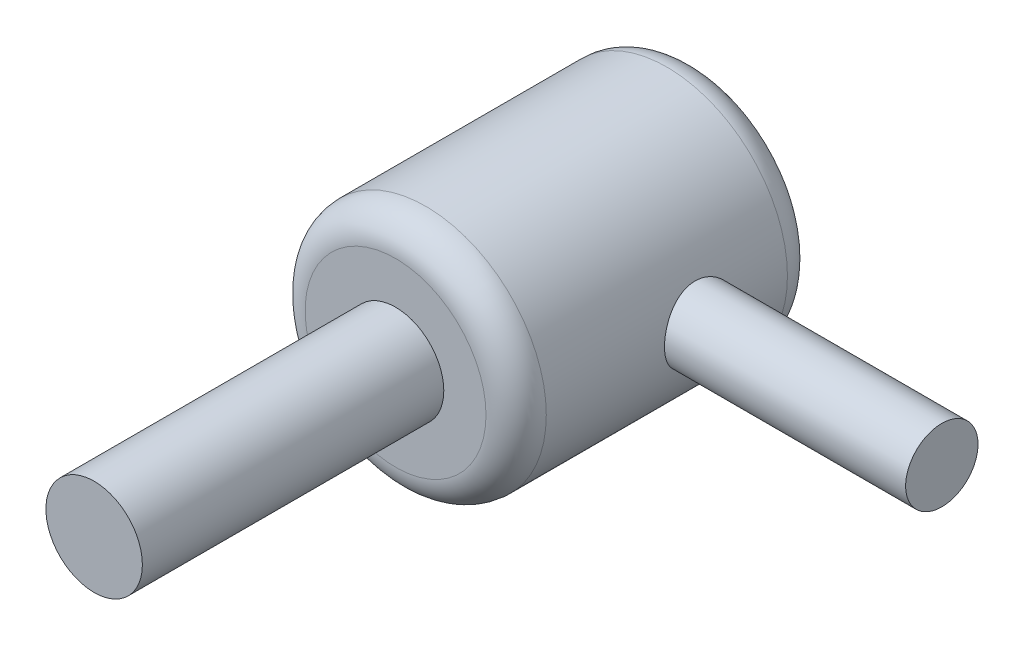
SolidWorks part; units mm, degrees
ref_plane "Płaszczyzna przednia" through (0, 0, 0) normal (0, 0, 1) x (1, 0, 0)
ref_plane "Płaszczyzna górna" through (0, 0, 0) normal (0, 1, 0) x (1, 0, 0)
ref_plane "Płaszczyzna prawa" through (0, 0, 0) normal (1, 0, 0) x (0, 0, -1)
sketch "Szkic1" plane through (0, 0, 0) normal (0, 0, 1) x (1, 0, 0)
  circle A0 centre (0, 0) radius 20
extrude "Dodanie-wyciągnięcie1" add sketch "Szkic1" along normal blind 50
fillet "Zaokrąglenie1" radius 5 2 edges at (20, 0, 0) (20, 0, 50)
sketch "Szkic2" plane through (0, 0, 50) normal (0, 0, 1) x (1, 0, 0)
  circle A0 centre (0, 0) radius 8
extrude "Dodanie-wyciągnięcie2" add sketch "Szkic2" along normal blind 50
sketch "Szkic3" plane through (0, 0, 0) normal (1, 0, 0) x (0, 0, -1)
  circle A0 centre (-19.3895, 0) radius 6
extrude "Dodanie-wyciągnięcie3" add sketch "Szkic3" along normal blind 60
